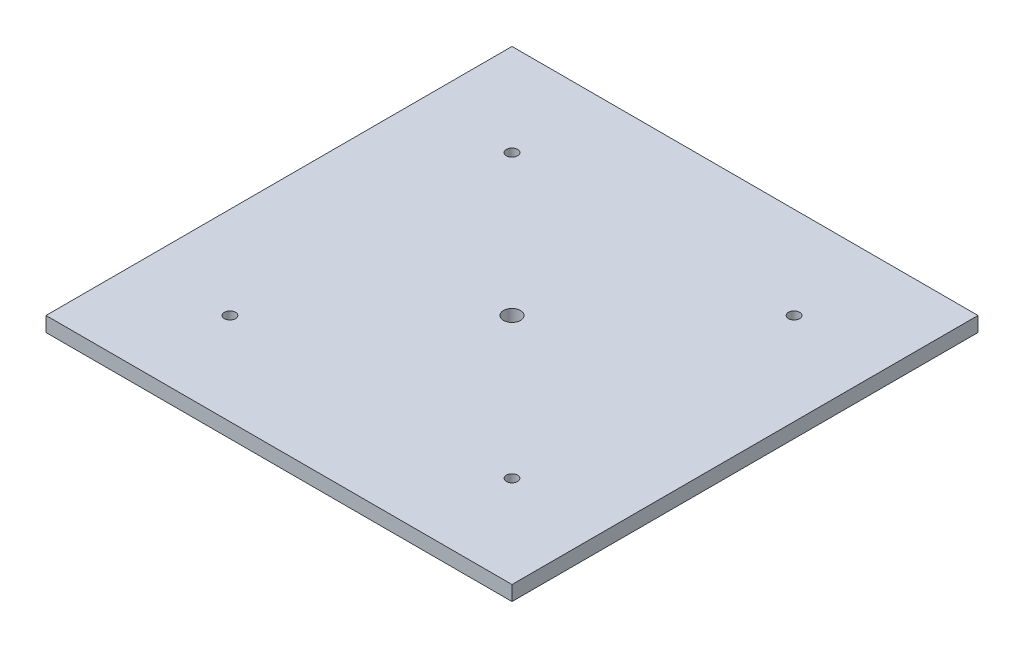
SolidWorks part; units mm, degrees
material "Pine"
ref_plane "Front" through (0, 0, 0) normal (0, 0, 1) x (1, 0, 0)
ref_plane "Top" through (0, 0, 0) normal (0, 1, 0) x (1, 0, 0)
ref_plane "Right" through (0, 0, 0) normal (1, 0, 0) x (0, 0, -1)
sketch "Sketch1" plane through (0, 0, 0) normal (0, 1, 0) x (1, 0, 0)
  line L1 (-100, 100) -> (100, 100)
  line L2 (-100, 100) -> (-100, -100)
  line L3 (-100, -100) -> (100, -100)
  line L4 (100, 100) -> (100, -100)
  point P4 (0, 0)
  point P5 (0, 100)
  point P7 (100, 0)
  point P8 (-14.2157, 10)
  dimension "D1" = 200
  dimension "D2" = 200
extrude "Boss-Extrude1" add sketch "Sketch1" along normal blind 6.35
sketch "Sketch2" plane through (0, 6.35, 0) normal (0, 1, 0) x (1, 0, 0)
  circle A0 centre (0, 0) radius 3.675
  dimension "D1" = 7.35
extrude "Cut-Extrude1" cut sketch "Sketch2" against normal through all
sketch "Sketch3" plane through (0, 6.35, 0) normal (0, 1, 0) x (1, 0, 0)
  line L1 (-60.53, 60.53) -> (60.53, 60.53) construction
  line L2 (-60.53, 60.53) -> (-60.53, -60.53) construction
  line L3 (-60.53, -60.53) -> (60.53, -60.53) construction
  line L4 (60.53, 60.53) -> (60.53, -60.53) construction
  point P4 (0, 60.53)
  point P5 (-60.53, 0)
  dimension "D1" = 121.06
  dimension "D2" = 121.06
hole_wizard "M4 Clearance Hole1" positions "3DSketch1" profile "Sketch4" hole size "M4" standard "ANSI Metric"
sketch3d "3DSketch1"
  point P0 (-60.53, 6.35, -60.53)
  point P3 (60.53, 6.35, -60.53)
  point P6 (60.53, 6.35, 60.53)
  point P9 (-60.53, 6.35, 60.53)
sketch "Sketch4" plane through (-60.53, 6.35, -60.53) normal (1, 0, 0) x (0, 0, 1)
  line L0 (0, 0) -> (0, 7.7911)
  line L1 (0, 7.7911) -> (2.4, 6.349)
  line L2 (2.4, 6.349) -> (2.4, 0)
  line L5 (2.4, 0) -> (0, 0)
  line L10 (0, 7.7911) -> (-2.4, 6.349) construction
  line L11 (0, -6.35) -> (0, 107.95) construction
  dimension "Hole Dia." = 4.8
  dimension "Hole Depth" = 6.349
  dimension "Drill Angle" = 118
